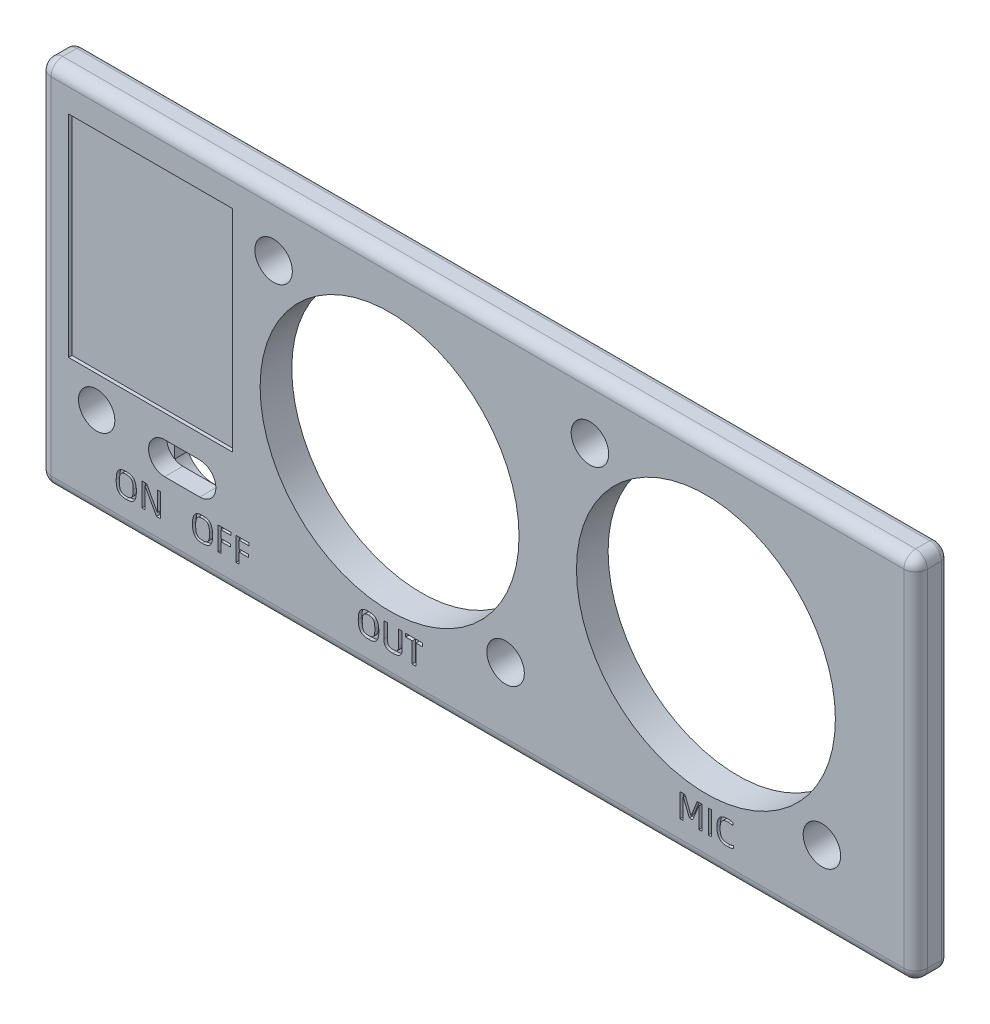
SolidWorks part; units mm, degrees
ref_plane "前视基准面" through (0, 0, 0) normal (0, 0, 1) x (1, 0, 0)
ref_plane "上视基准面" through (0, 0, 0) normal (0, 1, 0) x (1, 0, 0)
ref_plane "右视基准面" through (0, 0, 0) normal (1, 0, 0) x (0, 0, -1)
sketch "草图1" plane through (0, 0, 0) normal (0, 0, 1) x (1, 0, 0)
  line L1 (-37.4, 15.75) -> (37.4, 15.75)
  line L2 (-37.4, 15.75) -> (-37.4, -15.75)
  line L3 (-37.4, -15.75) -> (37.4, -15.75)
  line L4 (37.4, 15.75) -> (37.4, -15.75)
  line L5 (-37.4, 15.75) -> (37.4, -15.75) construction
  line L6 (-37.4, -15.75) -> (37.4, 15.75) construction
  point P0 (0, 0)
  dimension "D1" = 74.8
  dimension "D2" = 31.5
extrude "凸台-拉伸1" add sketch "草图1" along normal blind 2.7
fillet "圆角2" radius 1 4 edges at (37.4, -15.75, 1.35) (-37.4, -15.75, 1.35) (-37.4, 15.75, 1.35) (37.4, 15.75, 1.35)
fillet "圆角3" radius 1 8 edges at (37.1071, 15.4571, 2.7) (37.4, 0, 2.7) (37.1071, -15.4571, 2.7) (0, -15.75, 2.7) (-37.1071, -15.4571, 2.7) (-37.4, 0, 2.7) (-37.1071, 15.4571, 2.7) (0, 15.75, 2.7)
fillet "圆角4" radius 0.5 8 edges at (37.1071, 15.4571, 0) (37.4, 0, 0) (37.1071, -15.4571, 0) (0, -15.75, 0) (-37.1071, -15.4571, 0) (-37.4, 0, 0) (-37.1071, 15.4571, 0) (0, 15.75, 0)
sketch "草图2" plane through (0, 0, 2.7) normal (0, 0, 1) x (1, 0, 0)
  point P0 (32.5, -11.75)
  dimension "D1" = 32.5
  dimension "D2" = 11.75
sketch "草图3" plane through (0, 0, 2.7) normal (0, 0, 1) x (1, 0, 0)
  circle A0 centre (19.5, 0.75) radius 11.05
  circle A1 centre (29.4, -9.15) radius 1.6
  circle A2 centre (9.6, 10.65) radius 1.6
  circle A3 centre (-7.5, 0.75) radius 11.05
  circle A4 centre (2.4, -9.15) radius 1.6
  circle A5 centre (-17.4, 10.65) radius 1.6
  circle A6 centre (-32.5, -7.94) radius 1.55
  dimension "D1" = 22.1
  dimension "D3" = 3.2
  dimension "D5" = 3.2
  dimension "D11" = 3.1
  dimension "D2" = 12.5
  dimension "D4" = 9.9
  dimension "D6" = 9.9
  dimension "D7" = 9.9
  dimension "D8" = 9.9
  dimension "D9" = 13
  dimension "D12" = 65
  dimension "D17" = 3.81
  dimension "D10" = 2
extrude "切除-拉伸1" cut sketch "草图3" against normal up to next
sketch "草图4" plane through (0, 0, 0) normal (0, 0, -1) x (-1, 0, 0)
  line L0 (27.4, -7.4126) -> (27.4, -9.7874)
  arc A0 (27.4, -7.4126) -> (27.4, -9.7874) centre (25.2, -8.6) ccw
  point P5 (25.2, -8.6)
  dimension "D1" = 5
  dimension "D2" = 57.7
  dimension "D3" = 3.15
  dimension "D4" = 2.2
sketch "草图7" plane through (0, 0, 2.7) normal (0, 0, 1) x (1, 0, 0)
  line L0 (-26.7, -8.6) -> (-23.7, -8.6) construction
  line L1 (-26.7, -7.23) -> (-23.7, -7.23)
  line L2 (-26.7, -9.97) -> (-23.7, -9.97)
  arc A7 (-26.7, -7.23) -> (-26.7, -9.97) centre (-26.7, -8.6) ccw
  arc A8 (-23.7, -9.97) -> (-23.7, -7.23) centre (-23.7, -8.6) ccw
  point P17 (-25.2, -8.6)
  dimension "D3" = 3.15
  dimension "D13" = 1.37
  dimension "D2" = 57.7
  dimension "D14" = 3
sketch "草图5" plane through (0, 0, 2.7) normal (0, 0, 1) x (1, 0, 0)
  line L0 (-7.5, 0.75) -> (-7.5, -19.6631) construction
  line L1 (19.5, 0.75) -> (19.5, -19.6631) construction
  line L2 (-18.0794, -13.25) -> (3.0794, -13.25) construction
  line L3 (9.2729, -13.25) -> (29.7271, -13.25) construction
  line L4 (-36.4, -14.75) -> (36.4, -14.75) construction
  line L5 (-25.2, -9.97) -> (-25.2, -17.2636) construction
  line L7 (5.8568, -13.25) -> (-56.2568, -13.25) construction
  text T0 "OUT" font "阿里巴巴普惠体 2.0 65 Medium" height 2
  text T1 "MIC" font "阿里巴巴普惠体 2.0 55 Regular" height 2
  text T2 "ON   OFF" font "阿里巴巴普惠体 2.0 55 Regular" height 2
  point P9 (-7.5, -13.25)
  point P10 (19.5, -13.25)
  point P22 (-25.2, -13.25)
  dimension "D1" = 1.5
  dimension "D2" = 1.5
  dimension "D3" = 1.5
  dimension "D4" = 57.7
extrude "切除-拉伸3" cut sketch "草图5" against normal blind 0.3
sketch "草图6" plane through (0, 0, 2.7) normal (0, 0, 1) x (1, 0, 0)
  line L0 (-36.4, 14.75) -> (-36.4, -14.75) construction
  line L1 (-34.9, 12.75) -> (-20.9, 12.75)
  line L2 (-34.9, 12.75) -> (-34.9, -5.25)
  line L3 (-34.9, -5.25) -> (-20.9, -5.25)
  line L4 (-20.9, 12.75) -> (-20.9, -5.25)
  line L5 (36.4, 14.75) -> (-36.4, 14.75) construction
  dimension "D1" = 18
  dimension "D2" = 14
  dimension "D3" = 1.5
  dimension "D4" = 2
extrude "切除-拉伸4" cut sketch "草图6" against normal blind 0.3
extrude "切除-拉伸7" cut sketch "草图4" against normal blind 1.15
extrude "切除-拉伸8" cut sketch "草图7" against normal up to surface (1.55 mm away) up to face at (-25.05, -8.6, 1.15)
equation "\"D1@草图2\"=75/2-5"
equation "\"dim.x.width_internal\"= 75"
equation "\"dim.x.retract\"= 0.2"
equation "\"dim.y.height_internal\"= 31.7"
equation "\"dim.y.retract\"= 0.2"
equation "\"D1@草图1\"=\"dim.x.width_internal\"-\"dim.x.retract\""
equation "\"D2@草图1\"=\"dim.y.height_internal\"-\"dim.y.retract\""
equation "\"D2@草图2\"=\"dim.y.height_internal\" / 2 - 2.5 - 1.6"
equation "\"D4@草图3\"=19.8/2"
equation "\"D6@草图3\"=19.8/2"
equation "\"D7@草图3\"=19.8/2"
equation "\"D8@草图3\"=19.8/2"
